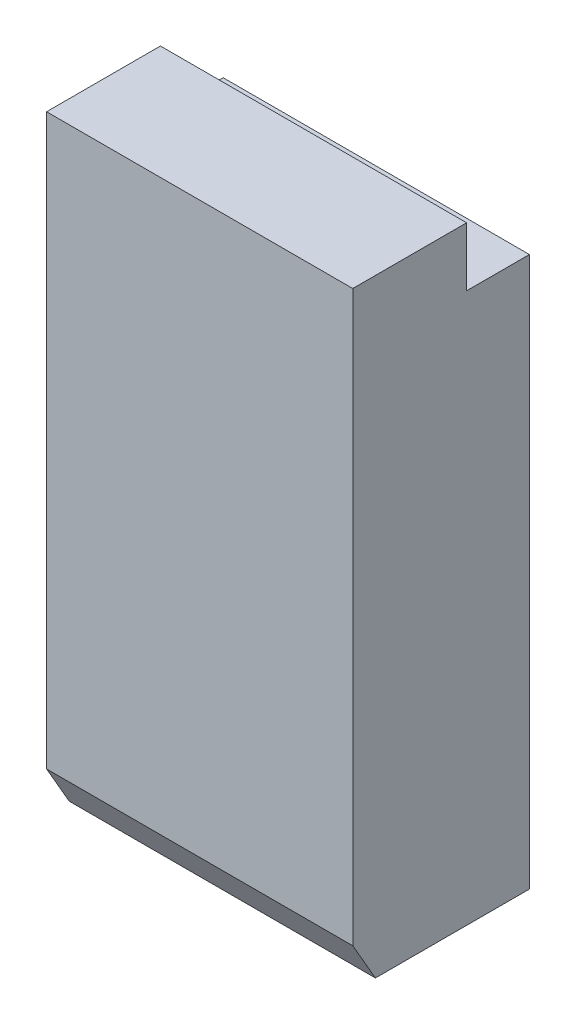
SolidWorks part; units mm, degrees
material "PET-G"
ref_plane "Спереди" through (0, 0, 0) normal (0, 0, 1) x (1, 0, 0)
ref_plane "Сверху" through (0, 0, 0) normal (0, 1, 0) x (1, 0, 0)
ref_plane "Справа" through (0, 0, 0) normal (1, 0, 0) x (0, 0, -1)
sketch "Эскиз1" plane through (0, 0, 0) normal (1, 0, 0) x (0, 0, -1)
  line L0 (0, 0) -> (0, 1.5)
  line L1 (0, 1.5) -> (2.9, 1.5)
  line L2 (2.9, 1.5) -> (2.9, 0)
  line L3 (2.9, 0) -> (4.5, 0)
  line L4 (4.5, 0) -> (4.5, -14)
  line L5 (4.5, -14) -> (0, -14)
  line L6 (0, -14) -> (0, 0)
  line L7 (2.9, 0) -> (0, 0) construction
  dimension "D1" = 2.9
  dimension "D2" = 1.5
  dimension "D3" = 4.5
  dimension "D4" = 14
extrude "Бобышка-Вытянуть1" add sketch "Эскиз1" along normal mid plane 7.8
chamfer "Фаска1" distance 1 angle 30 1 edges at (0, -14, 0)
